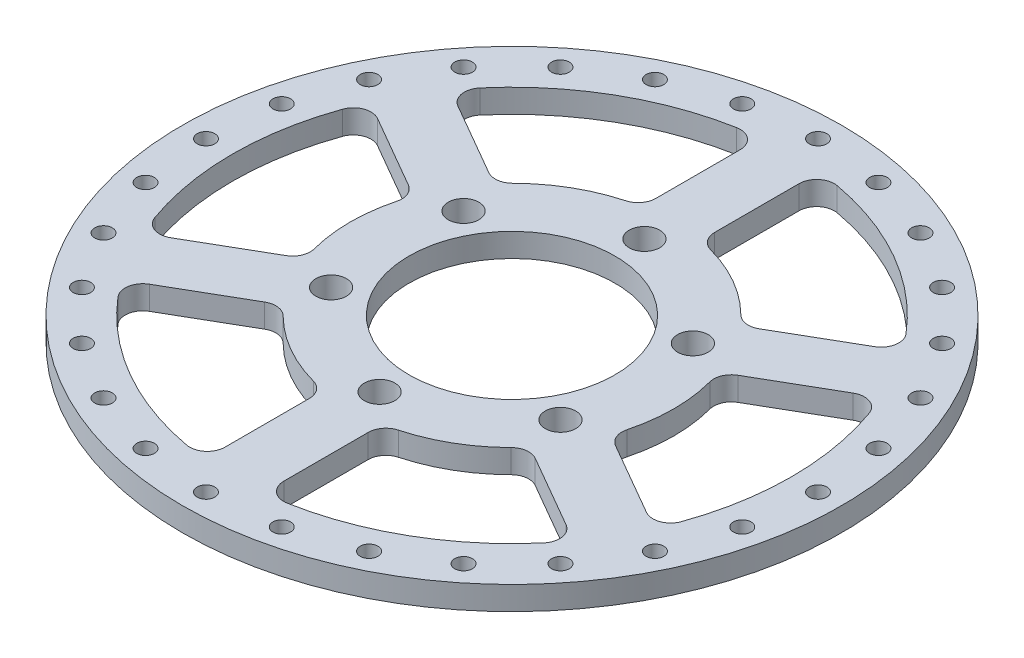
SolidWorks part; units mm, degrees
material "Thornel Mat VMA"
ref_plane "前视基准面" through (0, 0, 0) normal (0, 0, 1) x (1, 0, 0)
ref_plane "上视基准面" through (0, 0, 0) normal (0, 1, 0) x (1, 0, 0)
ref_plane "右视基准面" through (0, 0, 0) normal (1, 0, 0) x (0, 0, -1)
sketch "草图1" plane through (0, 0, 0) normal (0, 1, 0) x (1, 0, 0)
  line L0 (0, 27.5) -> (0, 47.5) construction
  line L1 (-5, 47.2361) -> (-5, 27.0416)
  line L2 (5, 47.2361) -> (5, 27.0416)
  line L3 (38.4077, 27.9482) -> (20.9187, 17.8509)
  line L4 (43.4077, 19.2879) -> (25.9187, 9.1907)
  line L5 (43.4077, -19.2879) -> (25.9187, -9.1907)
  line L6 (38.4077, -27.9482) -> (20.9187, -17.8509)
  line L7 (5, -47.2361) -> (5, -27.0416)
  line L8 (-5, -47.2361) -> (-5, -27.0416)
  line L9 (-38.4077, -27.9482) -> (-20.9187, -17.8509)
  line L10 (-43.4077, -19.2879) -> (-25.9187, -9.1907)
  line L11 (-43.4077, 19.2879) -> (-25.9187, 9.1907)
  line L12 (-38.4077, 27.9482) -> (-20.9187, 17.8509)
  circle A0 centre (0, 0) radius 56
  circle A1 centre (0, 0) radius 52 construction
  circle A2 centre (0, 0) radius 47.5
  circle A3 centre (0, 52) radius 1.5
  circle A4 centre (11.5711, 50.6963) radius 1.5
  circle A5 centre (22.562, 46.8504) radius 1.5
  circle A6 centre (32.4215, 40.6552) radius 1.5
  circle A7 centre (40.6552, 32.4215) radius 1.5
  circle A8 centre (46.8504, 22.562) radius 1.5
  circle A9 centre (50.6963, 11.5711) radius 1.5
  circle A10 centre (52, 0) radius 1.5
  circle A11 centre (50.6963, -11.5711) radius 1.5
  circle A12 centre (46.8504, -22.562) radius 1.5
  circle A13 centre (40.6552, -32.4215) radius 1.5
  circle A14 centre (32.4215, -40.6552) radius 1.5
  circle A15 centre (22.562, -46.8504) radius 1.5
  circle A16 centre (11.5711, -50.6963) radius 1.5
  circle A17 centre (0, -52) radius 1.5
  circle A18 centre (-11.5711, -50.6963) radius 1.5
  circle A19 centre (-22.562, -46.8504) radius 1.5
  circle A20 centre (-32.4215, -40.6552) radius 1.5
  circle A21 centre (-40.6552, -32.4215) radius 1.5
  circle A22 centre (-46.8504, -22.562) radius 1.5
  circle A23 centre (-50.6963, -11.5711) radius 1.5
  circle A24 centre (-52, 0) radius 1.5
  circle A25 centre (-50.6963, 11.5711) radius 1.5
  circle A26 centre (-46.8504, 22.562) radius 1.5
  circle A27 centre (-40.6552, 32.4215) radius 1.5
  circle A28 centre (-32.4215, 40.6552) radius 1.5
  circle A29 centre (-22.562, 46.8504) radius 1.5
  circle A30 centre (-11.5711, 50.6963) radius 1.5
  circle A31 centre (0, 0) radius 22.5 construction
  circle A32 centre (0, 22.5) radius 2.6
  circle A33 centre (19.4856, 11.25) radius 2.6
  circle A34 centre (19.4856, -11.25) radius 2.6
  circle A35 centre (0, -22.5) radius 2.6
  circle A36 centre (-19.4856, -11.25) radius 2.6
  circle A37 centre (-19.4856, 11.25) radius 2.6
  circle A38 centre (0, 0) radius 17.5
  circle A39 centre (0, 0) radius 27.5
  point P63 (0, 0)
  point P77 (0, 0)
  point P106 (0, 0)
  dimension "D1" = 112
  dimension "D2" = 104
  dimension "D3" = 95
  dimension "D4" = 3
  dimension "D6" = 45
  dimension "D7" = 5.2
  dimension "D9" = 35
  dimension "D10" = 55
  dimension "D11" = 10
  dimension "D5" = 28
  dimension "D8" = 6
  dimension "D12" = 6
extrude "凸台-拉伸1" add sketch "草图1" along normal blind 4 contours A39 A38 A37 A36 A35 A34 A33 A32 | A39 L8 A2 L7 | A0 A30 A29 A28 A27 A26 A25 A24 A23 A22 A21 A20 A19 A18 A17 A16 A15 A14 A13 A12 A11 A10 A9 A8 A7 A6 | A39 L10 A2 L9 | A39 L12 A2 L11 | A39 L2 A2 L1 | A39 L4 A2 L3 | A39 L6 A2 L5
fillet "圆角1" radius 3 24 edges at (5, 2, 27.0416) (5, 2, 47.2361) (38.4077, 2, 27.9482) (20.9187, 2, 17.8509) (43.4077, 2, -19.2879) (25.9187, 2, -9.1907) (25.9187, 2, 9.1907) (43.4077, 2, 19.2879) (5, 2, -47.2361) (5, 2, -27.0416) (20.9187, 2, -17.8509) (38.4077, 2, -27.9482) (-38.4077, 2, -27.9482) (-20.9187, 2, -17.8509) (-5, 2, -47.2361) (-43.4077, 2, 19.2879) (-25.9187, 2, 9.1907) (-25.9187, 2, -9.1907) (-43.4077, 2, -19.2879) (-5, 2, 47.2361) (-5, 2, 27.0416) (-20.9187, 2, 17.8509) (-38.4077, 2, 27.9482) (-5, 2, -27.0416)
